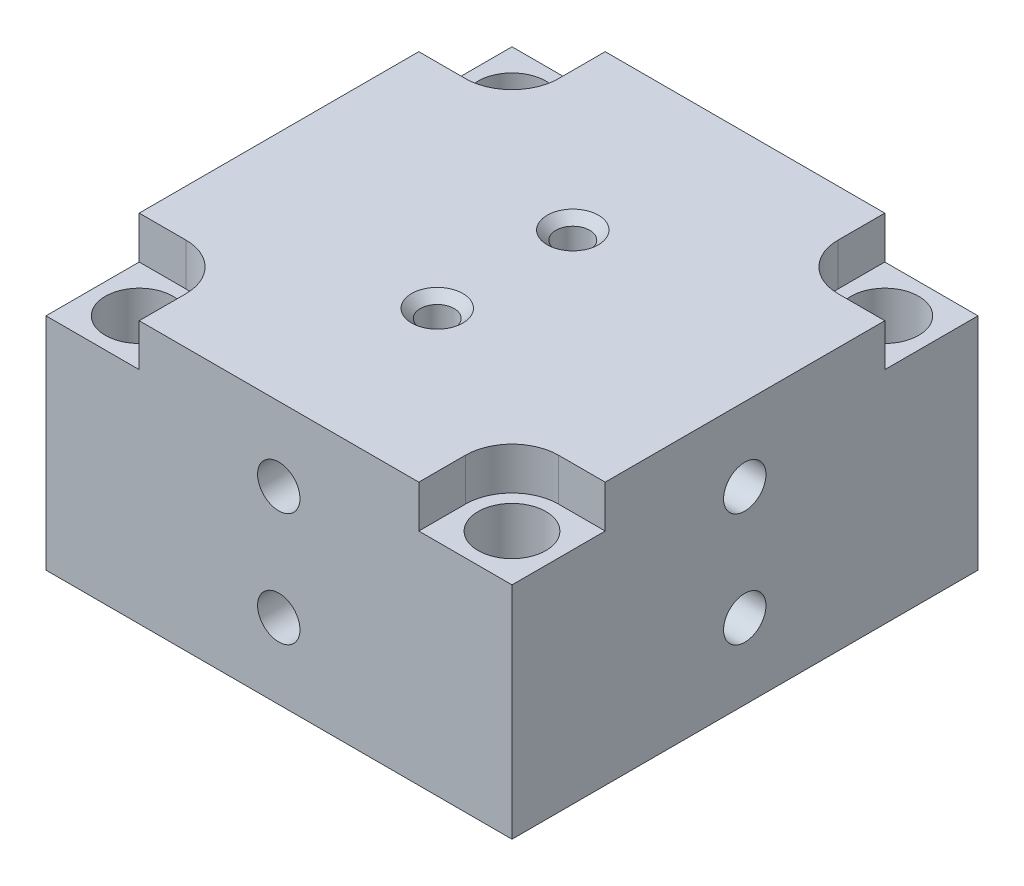
SolidWorks part; units mm, degrees
material "1060 合金"
ref_plane "前视基准面" through (0, 0, 0) normal (0, 0, 1) x (1, 0, 0)
ref_plane "上视基准面" through (0, 0, 0) normal (0, 1, 0) x (1, 0, 0)
ref_plane "右视基准面" through (0, 0, 0) normal (1, 0, 0) x (0, 0, -1)
other "Configuration Table"
sketch "草图1" plane through (0, 0, 0) normal (0, 1, 0) x (1, 0, 0)
  line L1 (-27.5, 27.5) -> (27.5, 27.5)
  line L2 (-27.5, 27.5) -> (-27.5, -27.5)
  line L3 (-27.5, -27.5) -> (27.5, -27.5)
  line L4 (27.5, 27.5) -> (27.5, -27.5)
  line L5 (-27.5, 27.5) -> (27.5, -27.5) construction
  line L6 (-27.5, -27.5) -> (27.5, 27.5) construction
  point P0 (0, 0)
  dimension "D1" = 55
  dimension "D2" = 55
extrude "凸台-拉伸1" add sketch "草图1" along normal mid plane 31
sketch "草图2" plane through (0, 15.5, 0) normal (0, 1, 0) x (1, 0, 0)
  line L16 (16.5, 22) -> (16.5, 27.5)
  line L17 (-22, 22) -> (22, 22) construction
  line L18 (-22, 22) -> (-22, -22) construction
  line L19 (-22, -22) -> (22, -22) construction
  line L20 (22, 22) -> (22, -22) construction
  line L21 (-22, 22) -> (22, -22) construction
  line L22 (-22, -22) -> (22, 22) construction
  line L23 (27.5, 27.5) -> (-27.5, 27.5) construction
  line L24 (16.5, 27.5) -> (27.5, 27.5)
  line L25 (22, 16.5) -> (27.5, 16.5)
  line L26 (27.5, -27.5) -> (27.5, 27.5) construction
  line L27 (27.5, 16.5) -> (27.5, 27.5)
  line L28 (22, -16.5) -> (27.5, -16.5)
  line L29 (27.5, -16.5) -> (27.5, -27.5)
  line L30 (16.5, -27.5) -> (27.5, -27.5)
  line L31 (16.5, -22) -> (16.5, -27.5)
  line L32 (-16.5, -22) -> (-16.5, -27.5)
  line L33 (-16.5, -27.5) -> (-27.5, -27.5)
  line L34 (-27.5, -16.5) -> (-27.5, -27.5)
  line L35 (-22, -16.5) -> (-27.5, -16.5)
  line L36 (-22, 16.5) -> (-27.5, 16.5)
  line L37 (-27.5, 16.5) -> (-27.5, 27.5)
  line L38 (-16.5, 27.5) -> (-27.5, 27.5)
  line L39 (-16.5, 22) -> (-16.5, 27.5)
  arc A0 (16.5, 22) -> (22, 16.5) centre (22, 22) ccw
  arc A1 (22, -16.5) -> (16.5, -22) centre (22, -22) ccw
  arc A2 (-16.5, -22) -> (-22, -16.5) centre (-22, -22) ccw
  arc A3 (-22, 16.5) -> (-16.5, 22) centre (-22, 22) ccw
  point P0 (0, 0)
  point P38 (0, 0)
  dimension "D3" = 11
  dimension "D1" = 44
  dimension "D2" = 44
  dimension "D4" = 4
extrude "切除-拉伸1" cut sketch "草图2" against normal blind 5
sketch "草图4" plane through (0, 10.5, 0) normal (0, 1, 0) x (1, 0, 0)
  circle A0 centre (22, 22) radius 4
  arc A1 (16.5, 22) -> (22, 16.5) centre (22, 22) ccw construction
  circle A2 centre (22, -22) radius 4
  circle A3 centre (-22, -22) radius 4
  circle A4 centre (-22, 22) radius 4
  point P14 (0, 0)
  dimension "D1" = 8
  dimension "D2" = 4
extrude "切除-拉伸2" cut sketch "草图4" against normal through all
hole_wizard "M6 螺纹孔1" positions "草图5" profile "草图6" tap size "M6" standard "GB"
sketch "草图5" plane through (0, 0, 27.5) normal (0, 0, 1) x (1, 0, 0)
  point P0 (-0.0273, -6.6015)
  point P3 (-0.0273, -6.6015)
sketch "草图6" plane through (-0.0273, -6.6015, 27.5) normal (1, 0, 0) x (0, -1, 0)
  line L0 (0, 0) -> (0, 8.5022)
  line L1 (0, 8.5022) -> (2.5, 7)
  line L2 (2.5, 7) -> (2.5, -0.5)
  line L3 (2.5, -0.5) -> (2, 0)
  line L5 (2, 0) -> (0, 0)
  line L6 (-2.5, -0.5) -> (-2, 0) construction
  line L10 (0, 8.5022) -> (-2.5, 7) construction
  line L11 (0, -6.35) -> (0, 107.95) construction
  dimension "螺纹孔钻头直径" = 5
  dimension "螺纹孔钻头深度" = 7
  dimension "近端锥形沉头孔直径" = 4
  dimension "近端锥形沉头孔角度" = 90
  dimension "导头角度" = 118
cosmetic thread "孔螺蚊线1" parameters "D1"=4, "D2"=6
pattern_circular "阵列(圆周)1" count 4 over 360 about axis through (0, 15.5, 0) along (0, 1, 0) skipping 1, 2, 3 of "M6 螺纹孔1"
hole_wizard "M6 螺纹孔2" positions "草图7" profile "草图8" tap size "M6" standard "GB"
sketch "草图7" plane through (0, 15.5, 0) normal (0, 1, 0) x (1, 0, 0)
  point P0 (-0.1826, 7.3581)
  point P3 (-0.1826, 7.3581)
sketch "草图8" plane through (-0.1826, 15.5, -7.3581) normal (1, 0, 0) x (0, 0, 1)
  line L0 (0, 0) -> (0, 8.2017)
  line L1 (0, 8.2017) -> (2, 7)
  line L2 (2, 7) -> (2, 1.025)
  line L3 (2, 1.025) -> (3.025, 0)
  line L5 (3.025, 0) -> (0, 0)
  line L6 (-2, 1.025) -> (-3.025, 0) construction
  line L10 (0, 8.2017) -> (-2, 7) construction
  line L11 (0, -6.35) -> (0, 107.95) construction
  dimension "螺纹孔钻头直径" = 4
  dimension "螺纹孔钻头深度" = 7
  dimension "近端锥形沉头孔直径" = 6.05
  dimension "近端锥形沉头孔角度" = 90
  dimension "导头角度" = 118
cosmetic thread "孔螺蚊线2" parameters "D1"=4, "D2"=6
sketch "草图9" plane through (0, 0, 27.5) normal (0, 0, 1) x (1, 0, 0)
  circle A0 centre (-0.0273, -6.6015) radius 15
  dimension "D1" = 30
pattern_linear "阵列(线性)3" count 2 spacing 16 along (0, 0, 1) of "M6 螺纹孔2"
pattern_linear "阵列(线性)4" count 2 spacing 13.4 along (0, 1, 0) of "M6 螺纹孔1"
pattern_circular "阵列(圆周)2" count 4 over 360 of "阵列(线性)4", "M6 螺纹孔1"
hole_wizard "M6 螺纹孔3" positions "草图12" profile "草图14" tap size "M6" standard "GB"
sketch "草图12" plane through (-6.5785, -15.5, 8.3867) normal (0, -1, 0) x (-1, 0, 0)
  point P0 (-6.5785, 8.1568)
  point P3 (-6.5785, 8.1568)
sketch "草图14" plane through (0, -15.5, 0.2299) normal (1, 0, 0) x (0, 0, -1)
  line L0 (0, 0) -> (0, 8.2017)
  line L1 (0, 8.2017) -> (2, 7)
  line L2 (2, 7) -> (2, 1.025)
  line L3 (2, 1.025) -> (3.025, 0)
  line L5 (3.025, 0) -> (0, 0)
  line L6 (-2, 1.025) -> (-3.025, 0) construction
  line L10 (0, 8.2017) -> (-2, 7) construction
  line L11 (0, -6.35) -> (0, 107.95) construction
  dimension "螺纹孔钻头直径" = 4
  dimension "螺纹孔钻头深度" = 7
  dimension "近端锥形沉头孔直径" = 6.05
  dimension "近端锥形沉头孔角度" = 90
  dimension "导头角度" = 118
cosmetic thread "孔螺纹线1" parameters "D1"=4, "D2"=6
